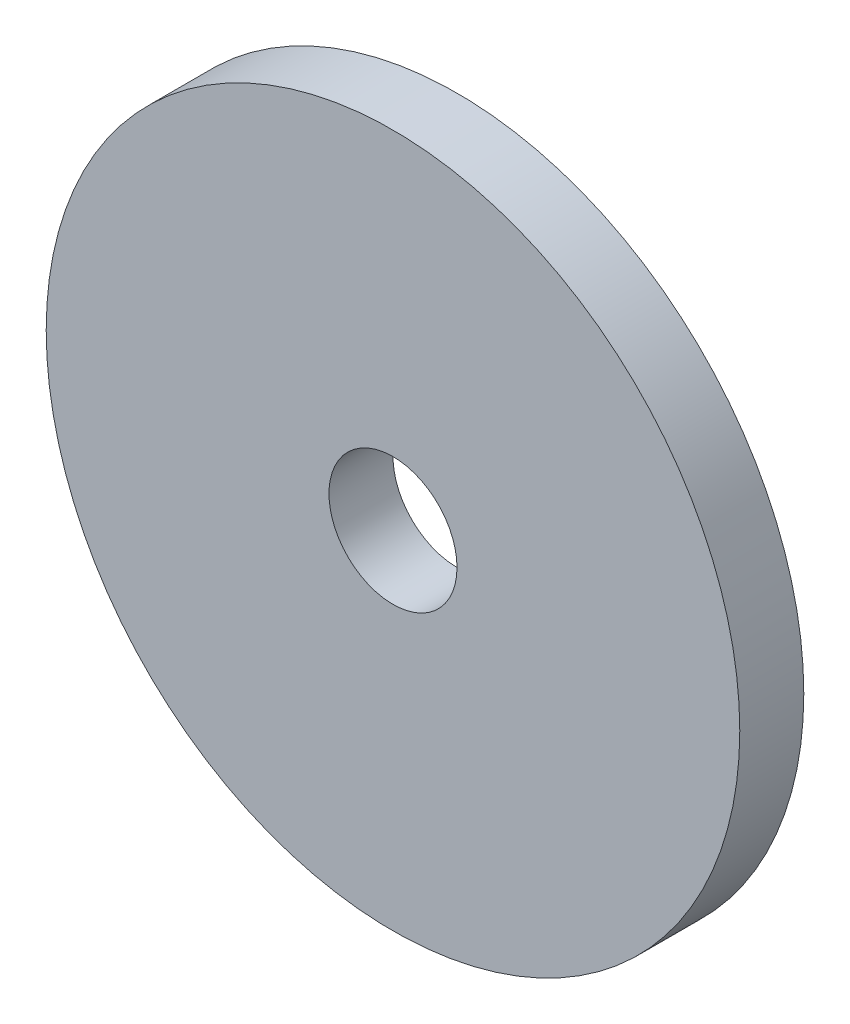
SolidWorks part; units mm, degrees
ref_plane "Piano frontale" through (0, 0, 0) normal (0, 0, 1) x (1, 0, 0)
ref_plane "Piano superiore" through (0, 0, 0) normal (0, 1, 0) x (1, 0, 0)
ref_plane "Piano destro" through (0, 0, 0) normal (1, 0, 0) x (0, 0, -1)
sketch "Schizzo1" plane through (0, 0, 0) normal (0, 0, 1) x (1, 0, 0)
  circle A0 centre (0, 0) radius 32.5
  circle A1 centre (0, 0) radius 6
  dimension "D1" = 65
  dimension "D2" = 12
extrude "Estrusione-Estrusione1" add sketch "Schizzo1" along normal mid plane 6
